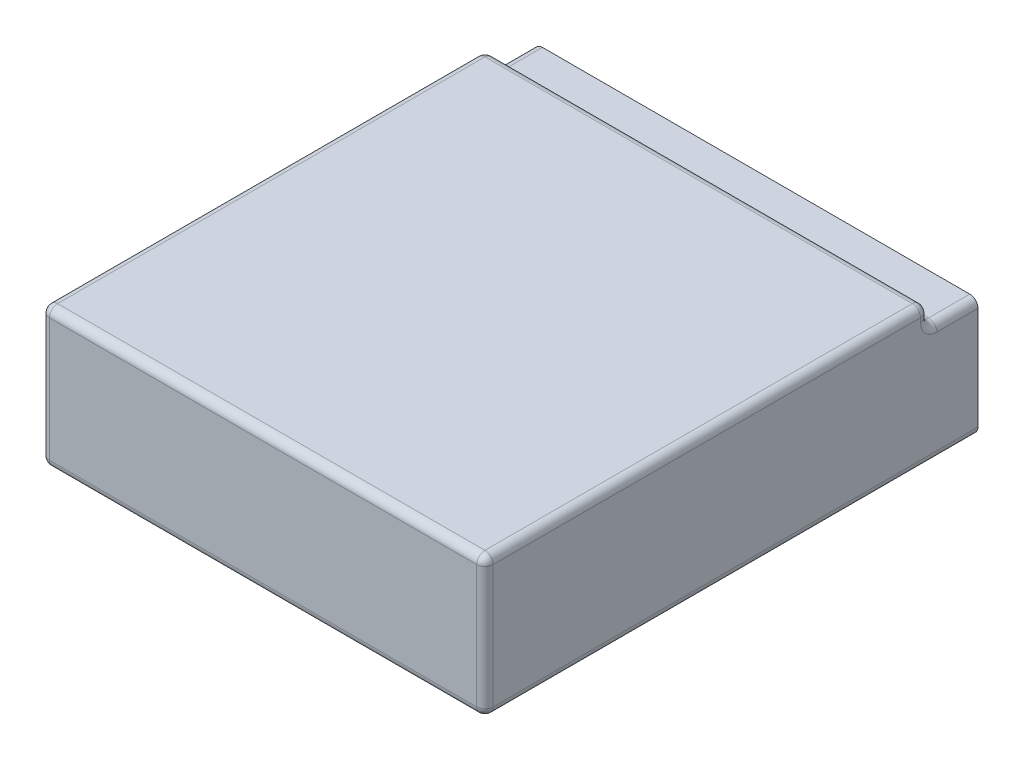
SolidWorks part; units mm, degrees
material "Custom Plastic"
ref_plane "Front Plane" through (0, 0, 0) normal (0, 0, 1) x (1, 0, 0)
ref_plane "Top Plane" through (0, 0, 0) normal (0, 1, 0) x (1, 0, 0)
ref_plane "Right Plane" through (0, 0, 0) normal (1, 0, 0) x (0, 0, -1)
sketch "Sketch1" plane through (0, 0, 0) normal (0, 1, 0) x (1, 0, 0)
  line L1 (-29.0445, 29.7706) -> (24.9555, 29.7706)
  line L2 (-29.0445, 29.7706) -> (-29.0445, -30.2294)
  line L3 (-29.0445, -30.2294) -> (24.9555, -30.2294)
  line L4 (24.9555, 29.7706) -> (24.9555, -30.2294)
extrude "Boss-Extrude1" add sketch "Sketch1" along normal blind 17
sketch "Sketch2" plane through (0, 17, 0) normal (0, 1, 0) x (1, 0, 0)
  line L1 (24.9555, 29.7706) -> (-29.0445, 29.7706) construction
  line L2 (-29.0445, 29.7706) -> (-29.0445, -30.2294) construction
  line L3 (-29.0445, 23.7706) -> (24.9555, 23.7706)
  line L4 (-29.0445, 23.7706) -> (-29.0445, 29.7706)
  line L5 (-29.0445, 29.7706) -> (24.9555, 29.7706)
  line L6 (24.9555, 23.7706) -> (24.9555, 29.7706)
  line L7 (24.9555, -30.2294) -> (24.9555, 29.7706) construction
extrude "Cut-Extrude1" cut sketch "Sketch2" against normal blind 2.5
fillet "Fillet1" radius 1 14 edges at (-29.0445, 14.5, -26.7706) (24.9555, 14.5, -26.7706) (-29.0445, 15.75, -23.7706) (24.9555, 15.75, -23.7706) (-2.0445, 14.5, -23.7706) (-2.0445, 17, -23.7706) (-29.0445, 0, 0.2294) (-29.0445, 17, 3.2294) (-2.0445, 0, 30.2294) (-2.0445, 17, 30.2294) (-29.0445, 8.5, 30.2294) (24.9555, 8.5, 30.2294) (24.9555, 0, 0.2294) (24.9555, 17, 3.2294)
